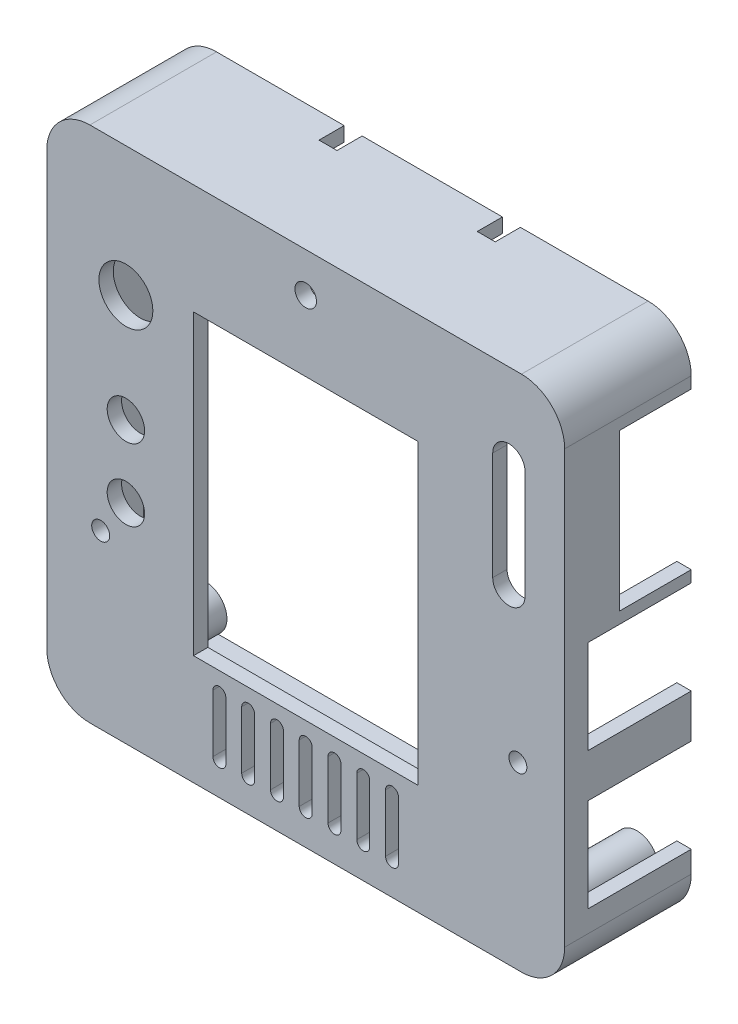
SolidWorks part; units mm, degrees
ref_plane "Front Plane" through (0, 0, 0) normal (0, 0, 1) x (1, 0, 0)
ref_plane "Top Plane" through (0, 0, 0) normal (0, 1, 0) x (1, 0, 0)
ref_plane "Right Plane" through (0, 0, 0) normal (1, 0, 0) x (0, 0, -1)
sketch "Sketch1" plane through (0, 0, 0) normal (0, 0, 1) x (1, 0, 0)
  line L0 (-30, -36) -> (30, -36)
  line L1 (36, -30) -> (36, 30)
  line L2 (30, 36) -> (-30, 36)
  line L3 (-36, 30) -> (-36, -30)
  arc A0 (30, -36) -> (36, -30) centre (30, -30) ccw
  arc A1 (36, 30) -> (30, 36) centre (30, 30) ccw
  arc A2 (-30, 36) -> (-36, 30) centre (-30, 30) ccw
  arc A3 (-36, -30) -> (-30, -36) centre (-30, -30) ccw
extrude "Boss-Extrude1" add sketch "Sketch1" along normal blind 17.6
sketch "Sketch2" plane through (0, 0, 0) normal (0, 0, 1) x (1, 0, 0)
  line L0 (-30, -34) -> (30, -34)
  line L1 (34, -30) -> (34, 30)
  line L2 (30, 34) -> (-30, 34)
  line L3 (-34, 30) -> (-34, -30)
  arc A0 (30, -34) -> (34, -30) centre (30, -30) ccw
  arc A1 (34, 30) -> (30, 34) centre (30, 30) ccw
  arc A2 (-30, 34) -> (-34, 30) centre (-30, 30) ccw
  arc A3 (-34, -30) -> (-30, -34) centre (-30, -30) ccw
extrude "Cut-Extrude1" cut sketch "Sketch2" along normal blind 15.6
ref_plane "Z+1_550" through (0, 0, 1.55) normal (0, 0, 1) x (1, 0, 0)
sketch "Sketch3" plane through (0, 0, 1.55) normal (0, 0, 1) x (1, 0, 0)
  circle A0 centre (-30, 30) radius 3
  circle A1 centre (30, 30) radius 2.5
  circle A2 centre (-30, -30) radius 3
  circle A3 centre (30, -30) radius 3
extrude "Boss-Extrude2" add sketch "Sketch3" along normal blind 14.05
sketch "Sketch4" plane through (0, 0, 1.55) normal (0, 0, 1) x (1, 0, 0)
  line L1 (27, 26) -> (33, 26)
  line L2 (27, 26) -> (27, 28.3)
  line L3 (27, 28.3) -> (33, 28.3)
  line L4 (33, 26) -> (33, 28.3)
extrude "Cut-Extrude2" cut sketch "Sketch4" along normal blind 14.05
sketch "Sketch5" plane through (0, 0, 1.55) normal (0, 0, 1) x (1, 0, 0)
  circle A0 centre (-30, 30) radius 1.1
  circle A1 centre (30, 30) radius 1.1
  circle A2 centre (-30, -30) radius 1.1
  circle A3 centre (30, -30) radius 1.1
extrude "Cut-Extrude3" cut sketch "Sketch5" along normal blind 12
ref_plane "Z+15_600" through (0, 0, 15.6) normal (0, 0, 1) x (1, 0, 0)
sketch "Sketch6" plane through (0, 0, 15.6) normal (0, 0, 1) x (1, 0, 0)
  line L0 (28.25, 24.5) -> (28.25, 9.5) construction
  line L1 (-15.6, -20.7) -> (15.6, -20.7)
  line L2 (-15.6, -20.7) -> (-15.6, 20.7)
  line L3 (-15.6, 20.7) -> (15.6, 20.7)
  line L4 (15.6, -20.7) -> (15.6, 20.7)
  line L5 (30.5, 24.5) -> (30.5, 9.5)
  line L6 (26, 24.5) -> (26, 9.5)
  line L7 (-12, -23.5) -> (-12, -31.5) construction
  line L8 (-11.1, -23.5) -> (-11.1, -31.5)
  line L9 (-12.9, -23.5) -> (-12.9, -31.5)
  line L10 (-8, -23.5) -> (-8, -31.5) construction
  line L11 (-7.1, -23.5) -> (-7.1, -31.5)
  line L12 (-8.9, -23.5) -> (-8.9, -31.5)
  line L13 (-4, -23.5) -> (-4, -31.5) construction
  line L14 (-3.1, -23.5) -> (-3.1, -31.5)
  line L15 (-4.9, -23.5) -> (-4.9, -31.5)
  line L16 (0, -23.5) -> (0, -31.5) construction
  line L17 (0.9, -23.5) -> (0.9, -31.5)
  line L18 (-0.9, -23.5) -> (-0.9, -31.5)
  line L19 (4, -23.5) -> (4, -31.5) construction
  line L20 (4.9, -23.5) -> (4.9, -31.5)
  line L21 (3.1, -23.5) -> (3.1, -31.5)
  line L22 (8, -23.5) -> (8, -31.5) construction
  line L23 (8.9, -23.5) -> (8.9, -31.5)
  line L24 (7.1, -23.5) -> (7.1, -31.5)
  line L25 (12, -23.5) -> (12, -31.5) construction
  line L26 (12.9, -23.5) -> (12.9, -31.5)
  line L27 (11.1, -23.5) -> (11.1, -31.5)
  circle A0 centre (-25, 18) radius 3.75
  circle A1 centre (-25, 3) radius 2.6
  circle A2 centre (-25, -7) radius 2.6
  circle A3 centre (0, 30.5) radius 1.5
  circle A4 centre (-28.5, -12.1) radius 1.25
  circle A5 centre (29.5, -11) radius 1.25
  arc A6 (30.5, 24.5) -> (26, 24.5) centre (28.25, 24.5) ccw
  arc A7 (26, 9.5) -> (30.5, 9.5) centre (28.25, 9.5) ccw
  arc A8 (-11.1, -23.5) -> (-12.9, -23.5) centre (-12, -23.5) ccw
  arc A9 (-12.9, -31.5) -> (-11.1, -31.5) centre (-12, -31.5) ccw
  arc A10 (-7.1, -23.5) -> (-8.9, -23.5) centre (-8, -23.5) ccw
  arc A11 (-8.9, -31.5) -> (-7.1, -31.5) centre (-8, -31.5) ccw
  arc A12 (-3.1, -23.5) -> (-4.9, -23.5) centre (-4, -23.5) ccw
  arc A13 (-4.9, -31.5) -> (-3.1, -31.5) centre (-4, -31.5) ccw
  arc A14 (0.9, -23.5) -> (-0.9, -23.5) centre (0, -23.5) ccw
  arc A15 (-0.9, -31.5) -> (0.9, -31.5) centre (0, -31.5) ccw
  arc A16 (4.9, -23.5) -> (3.1, -23.5) centre (4, -23.5) ccw
  arc A17 (3.1, -31.5) -> (4.9, -31.5) centre (4, -31.5) ccw
  arc A18 (8.9, -23.5) -> (7.1, -23.5) centre (8, -23.5) ccw
  arc A19 (7.1, -31.5) -> (8.9, -31.5) centre (8, -31.5) ccw
  arc A20 (12.9, -23.5) -> (11.1, -23.5) centre (12, -23.5) ccw
  arc A21 (11.1, -31.5) -> (12.9, -31.5) centre (12, -31.5) ccw
  point P4 (28.25, 17)
  point P23 (-12, -27.5)
  point P30 (-8, -27.5)
  point P37 (-4, -27.5)
  point P44 (0, -27.5)
  point P52 (4, -27.5)
  point P59 (8, -27.5)
  point P66 (12, -27.5)
  point P73 (0, 0)
extrude "Cut-Extrude4" cut sketch "Sketch6" along normal blind 2
sketch "Sketch7" plane through (0, 0, 0) normal (0, 0, 1) x (1, 0, 0)
  line L1 (33.5, -7.95) -> (37, -7.95)
  line L2 (33.5, -7.95) -> (33.5, 5.06)
  line L3 (33.5, 5.06) -> (37, 5.06)
  line L4 (37, -7.95) -> (37, 5.06)
  line L6 (33.5, -27) -> (37, -27)
  line L7 (33.5, -27) -> (33.5, -13.99)
  line L8 (33.5, -13.99) -> (37, -13.99)
  line L9 (37, -27) -> (37, -13.99)
extrude "Cut-Extrude5" cut sketch "Sketch7" along normal blind 14.35
sketch "Sketch8" plane through (0, 0, 0) normal (0, 0, 1) x (1, 0, 0)
  line L1 (33.5, 6.66) -> (37, 6.66)
  line L2 (33.5, 6.66) -> (33.5, 28.4)
  line L3 (33.5, 28.4) -> (37, 28.4)
  line L4 (37, 6.66) -> (37, 28.4)
extrude "Cut-Extrude6" cut sketch "Sketch8" along normal blind 10
sketch "Sketch9" plane through (0, 0, 0) normal (0, 0, 1) x (1, 0, 0)
  line L1 (-37, -25.3) -> (-33.5, -25.3)
  line L2 (-37, -25.3) -> (-37, -12.7)
  line L3 (-37, -12.7) -> (-33.5, -12.7)
  line L4 (-33.5, -25.3) -> (-33.5, -12.7)
extrude "Cut-Extrude7" cut sketch "Sketch9" along normal blind 6.135
sketch "Sketch10" plane through (0, 0, 0) normal (0, 0, 1) x (1, 0, 0)
  line L1 (-12.25, 33.5) -> (-9.75, 33.5)
  line L2 (-12.25, 33.5) -> (-12.25, 37)
  line L3 (-12.25, 37) -> (-9.75, 37)
  line L4 (-9.75, 33.5) -> (-9.75, 37)
  line L6 (9.75, 33.5) -> (12.25, 33.5)
  line L7 (9.75, 33.5) -> (9.75, 37)
  line L8 (9.75, 37) -> (12.25, 37)
  line L9 (12.25, 33.5) -> (12.25, 37)
extrude "Cut-Extrude8" cut sketch "Sketch10" along normal blind 3.5
